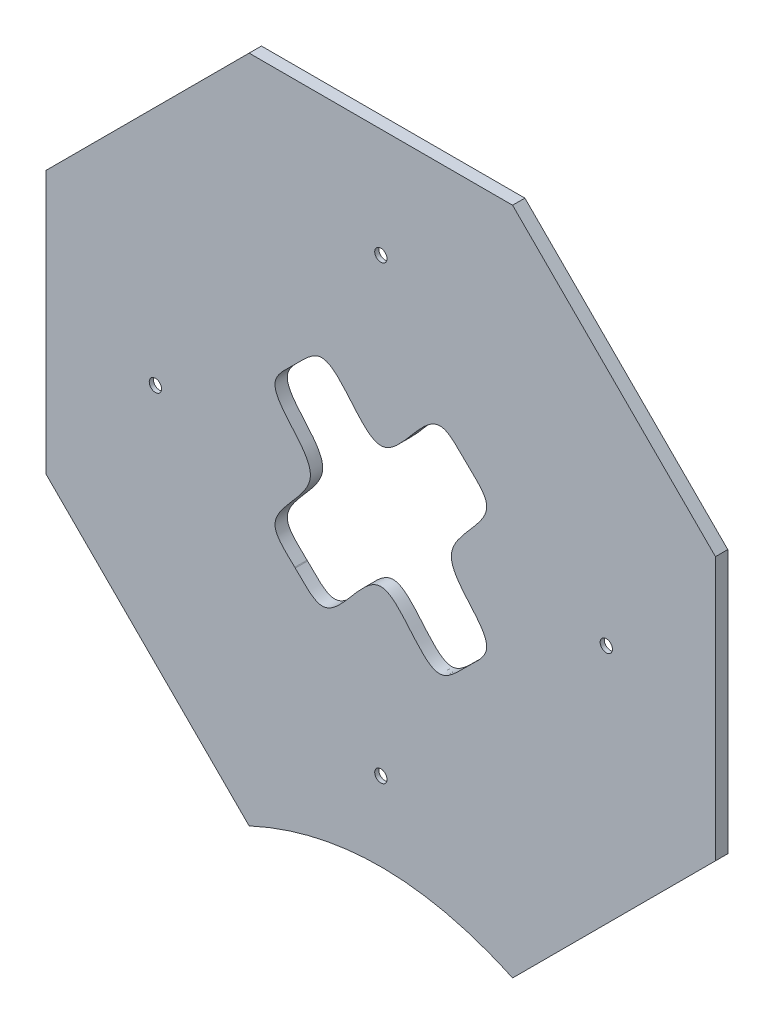
SolidWorks part; units mm, degrees
ref_plane "Front Plane" through (0, 0, 0) normal (0, 0, 1) x (1, 0, 0)
ref_plane "Top Plane" through (0, 0, 0) normal (0, 1, 0) x (1, 0, 0)
ref_plane "Right Plane" through (0, 0, 0) normal (1, 0, 0) x (0, 0, -1)
sketch "Sketch1" plane through (0, 0, 0) normal (0, 0, 1) x (1, 0, 0)
  line L0 (-32.1335, 81.6309) -> (32.1335, 81.6309)
  line L1 (32.1335, 81.6309) -> (81.6309, 32.1335)
  line L2 (81.6309, 32.1335) -> (81.6309, -32.1335)
  line L3 (81.6309, -32.1335) -> (32.1335, -81.6309)
  line L5 (-81.6309, -32.1335) -> (-81.6309, 32.1335)
  line L6 (-81.6309, 32.1335) -> (-32.1335, 81.6309)
  line L7 (-81.6309, -32.1335) -> (-32.1335, -81.6309)
  spline S0 degree 3 poles (-32.1335, -81.6309) (-26.3156, -78.9295) (-17.4585, -75.9069) (-6.4598, -74.367) (0.5039, -74.0955) (13.3814, -74.7374) (24.1945, -77.9193) (32.1335, -81.6309) knots 0 0 0 0 0.289772 0.418867 0.500126 0.604149 1 1 1 1
extrude "Boss-Extrude1" add sketch "Sketch1" along normal blind 3
sketch "Sketch2" plane through (0, 0, 3) normal (0, 0, 1) x (1, 0, 0)
  circle A0 centre (-39.2045, -39.2045) radius 1.5
  circle A1 centre (39.2045, -39.2045) radius 1.5
  circle A2 centre (39.2045, 39.2045) radius 1.5
  circle A3 centre (-39.2045, 39.2045) radius 1.5
extrude "Cut-Extrude1" cut sketch "Sketch2" against normal blind 3 contours A3 | A2 | A1 | A0
sketch "Sketch3" plane through (0, 0, 3) normal (0, 0, 1) x (1, 0, 0)
  circle A0 centre (0, 0) radius 30
  circle A1 centre (-30, 0) radius 15
  circle A2 centre (0, 30) radius 15
  circle A3 centre (30, 0) radius 15
  circle A4 centre (0, -30) radius 15
extrude "Cut-Extrude2" cut sketch "Sketch3" against normal blind 3 contours A0 A2 | A0 A2 | A4 A0 A3 A2 A1 | A0 A1 | A0 A4 | A0 A3 | A0 A3 | A0 A4 | A0 A1
sketch "Sketch4" plane through (0, 0, 3) normal (0, 0, 1) x (1, 0, 0)
  line L0 (-31.3996, -21.2591) -> (42.7738, -21.2591)
  line L1 (-26.25, 14.5237) -> (-26.25, -14.5237)
  line L2 (-26.25, 0) -> (-45, 0)
  line L4 (45, 0) -> (35.19, 0)
  circle A0 centre (-35.1862, 0) radius 18
  arc A1 (-26.25, 14.5237) -> (-26.25, -14.5237) centre (-30, 0) ccw construction
  arc A2 (26.25, -14.5237) -> (26.25, 14.5237) centre (30, 0) ccw construction
  circle A3 centre (35.19, 0) radius 18
extrude "Boss-Extrude6" add sketch "Sketch4" against normal blind 3
sketch "Sketch5" plane through (0, 0, 3) normal (0, 0, 1) x (1, 0, 0)
  circle A0 centre (0, -30) radius 15
extrude "Boss-Extrude7" add sketch "Sketch5" against normal blind 3
sketch "Sketch6" plane through (0, 0, 3) normal (0, 0, 1) x (1, 0, 0)
  circle A0 centre (0, 30) radius 15.2254
extrude "Boss-Extrude8" add sketch "Sketch6" against normal blind 3
sketch "Sketch7" plane through (0, 0, 3) normal (0, 0, 1) x (1, 0, 0)
  circle A0 centre (-46.2533, 32.1347) radius 1.5
  circle A1 centre (-52.1036, -20.8653) radius 1.5
  circle A2 centre (34.8964, -20.8653) radius 1.5
  circle A3 centre (34.8964, 32.1347) radius 1.5
extrude "Cut-Extrude4" cut sketch "Sketch7" against normal blind 3 contours A1 | A0 | A3 | A2
sketch "Sketch9" plane through (0, 0, 3) normal (0, 0, 1) x (1, 0, 0)
  circle A0 centre (0, 65.0045) radius 10
  circle A2 centre (0, -51.7736) radius 10
  circle A5 centre (-62.1862, 0) radius 10
  circle A6 centre (62.19, 0) radius 10
extrude "Cut-Extrude5" cut sketch "Sketch9" against normal blind 3 contours A5 | A0 | A6 | A2
sketch "Sketch10" plane through (0, 0, 3) normal (0, 0, 1) x (1, 0, 0)
  circle A0 centre (-48.6723, -29.5539) radius 19.1555
extrude "Boss-Extrude9" add sketch "Sketch10" against normal blind 3
sketch "Sketch11" plane through (0, 0, 3) normal (0, 0, 1) x (1, 0, 0)
  circle A0 centre (37.2125, -30.9758) radius 13.7568
extrude "Boss-Extrude10" add sketch "Sketch11" against normal blind 3
sketch "Sketch12" plane through (0, 0, 3) normal (0, 0, 1) x (1, 0, 0)
  circle A0 centre (38.5912, 36.4942) radius 11.5492
extrude "Boss-Extrude11" add sketch "Sketch12" against normal blind 3
sketch "Sketch14" plane through (0, 0, 3) normal (0, 0, 1) x (1, 0, 0)
  circle A0 centre (-42.2127, 37.6097) radius 9.6106
extrude "Boss-Extrude12" add sketch "Sketch14" against normal blind 3
sketch "Sketch15" plane through (0, 0, 3) normal (0, 0, 1) x (1, 0, 0)
  circle A0 centre (0, -51.7736) radius 14.0867
extrude "Boss-Extrude13" add sketch "Sketch15" against normal blind 3
sketch "Sketch16" plane through (0, 0, 3) normal (0, 0, 1) x (1, 0, 0)
  circle A0 centre (-63.7682, 0) radius 15.5437
extrude "Boss-Extrude14" add sketch "Sketch16" against normal blind 3
sketch "Sketch17" plane through (0, 0, 3) normal (0, 0, 1) x (1, 0, 0)
  circle A0 centre (-0.0588, 63.8451) radius 14.6815
extrude "Boss-Extrude17" add sketch "Sketch17" against normal blind 3
sketch "Sketch18" plane through (0, 0, 0) normal (0, 0, -1) x (-1, 0, 0)
  circle A0 centre (-63.5436, 0) radius 13.6141
extrude "Boss-Extrude18" add sketch "Sketch18" against normal blind 3
sketch "Sketch19" plane through (0, 0, 0) normal (0, 0, -1) x (-1, 0, 0)
  line L0 (0, 0) -> (0, -55)
  line L1 (0, 0) -> (0, 55)
  line L2 (0, 55) -> (0, 0)
  line L3 (0, 0) -> (55, 0)
  line L4 (0, 0) -> (-55, 0)
  circle A0 centre (0, 55) radius 1.5
  circle A1 centre (55, 0) radius 1.5
  circle A2 centre (0, -55) radius 1.5
  circle A3 centre (-55, 0) radius 1.5
extrude "Cut-Extrude6" cut sketch "Sketch19" against normal blind 10
sketch "Sketch20" plane through (0, 0, 0) normal (0, 0, -1) x (-1, 0, 0)
  circle A1 centre (0, 55) radius 5
  circle A2 centre (55, 0) radius 5
  circle A3 centre (0, -55) radius 5
  circle A4 centre (-55, 0) radius 5
extrude "Cut-Extrude8" cut sketch "Sketch20" against normal blind 2 contours A4 | A3 | A2 | A1
sketch "Sketch21" plane through (0, 0, 0) normal (0, 0, -1) x (-1, 0, 0)
  arc A0 (-14.7271, 26.1364) -> (-25.7791, 15.3439) centre (0, 0) ccw construction
  arc A1 (-14.7271, 26.1364) -> (14.7271, 26.1364) centre (0, 30) ccw construction
  arc A2 (25.7781, 15.3456) -> (14.7271, 26.1364) centre (0, 0) ccw construction
  arc A3 (25.7781, 15.3456) -> (25.7781, -15.3456) centre (35.1862, 0) ccw construction
  arc A4 (14.5237, -26.25) -> (25.7781, -15.3456) centre (0, 0) ccw construction
  arc A5 (14.5237, -26.25) -> (-14.5237, -26.25) centre (0, -30) ccw construction
  arc A6 (-25.7791, -15.3439) -> (-14.5237, -26.25) centre (0, 0) ccw construction
  arc A7 (-25.7791, -15.3439) -> (-25.7791, 15.3439) centre (-35.19, 0) ccw construction
  spline S0 degree 3 poles (-7.8581, 0.0019) (-30.6705, 13.0605) (-20.8149, 21.2531) (-11.928, 31.5454) (0, 2.954) (11.9277, 31.545) (20.8142, 21.2538) (30.6704, 13.0612) (7.8511, 0.0019) (30.7022, -13.1019) (20.7281, -21.329) (11.7946, -31.6225) (0, -3.378) (-11.7949, -31.6229) (-20.7288, -21.3283) (-30.7023, -13.1012) (-7.8581, 0.0019) (-30.6705, 13.0605) (-20.8149, 21.2531) knots -0.208024 -0.169846 -0.084923 0 0.03762 0.07524 0.165071 0.254901 0.292517 0.330132 0.415069 0.500006 0.538179 0.576352 0.665075 0.753798 0.791976 0.830154 0.915077 1 1.03762 1.07524 1.165071 only from (-25.7791, 15.3439) to (-25.7791, 15.3439)
extrude "Cut-Extrude11" cut sketch "Sketch21" against normal blind 14 contours S0
